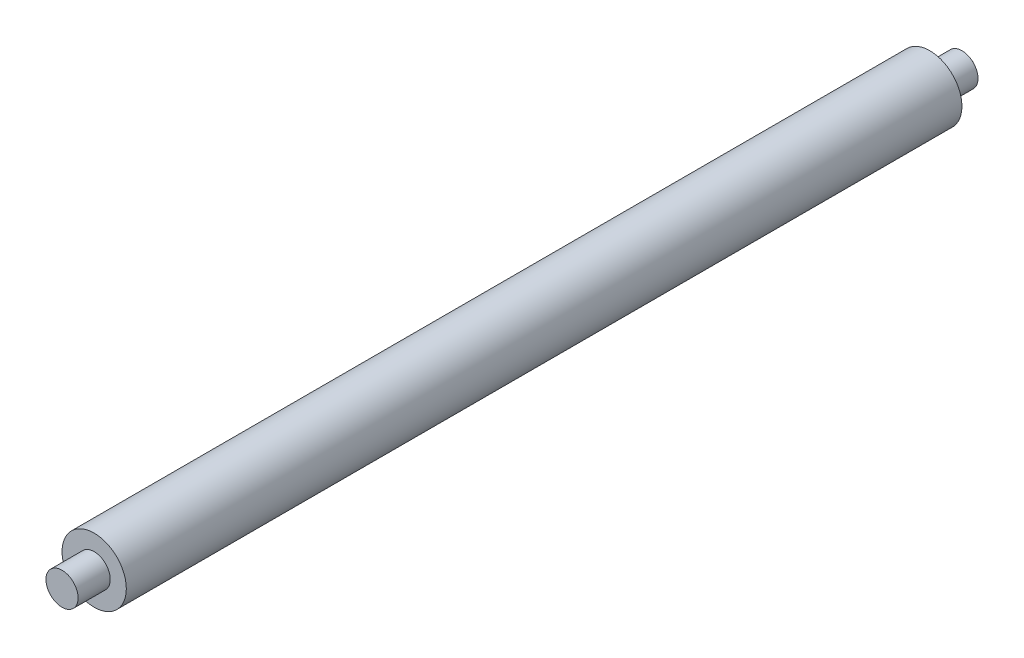
SolidWorks part; units mm, degrees
ref_plane "Front Plane" through (0, 0, 0) normal (0, 0, 1) x (1, 0, 0)
ref_plane "Top Plane" through (0, 0, 0) normal (0, 1, 0) x (1, 0, 0)
ref_plane "Right Plane" through (0, 0, 0) normal (1, 0, 0) x (0, 0, -1)
sketch "Sketch1" plane through (0, 0, 0) normal (0, 0, 1) x (1, 0, 0)
  circle A0 centre (0, 0) radius 2.5
  dimension "D1" = 5
extrude "Boss-Extrude1" add sketch "Sketch1" along normal blind 5
sketch "Sketch2" plane through (0, 0, 5) normal (0, 0, 1) x (1, 0, 0)
  circle A0 centre (0, 0) radius 5
  dimension "D1" = 10
extrude "Boss-Extrude2" add sketch "Sketch2" along normal blind 130
sketch "Sketch3" plane through (0, 0, 135) normal (0, 0, 1) x (1, 0, 0)
  circle A0 centre (0, 0) radius 2.5
  dimension "D1" = 5
extrude "Boss-Extrude3" add sketch "Sketch3" along normal blind 5
